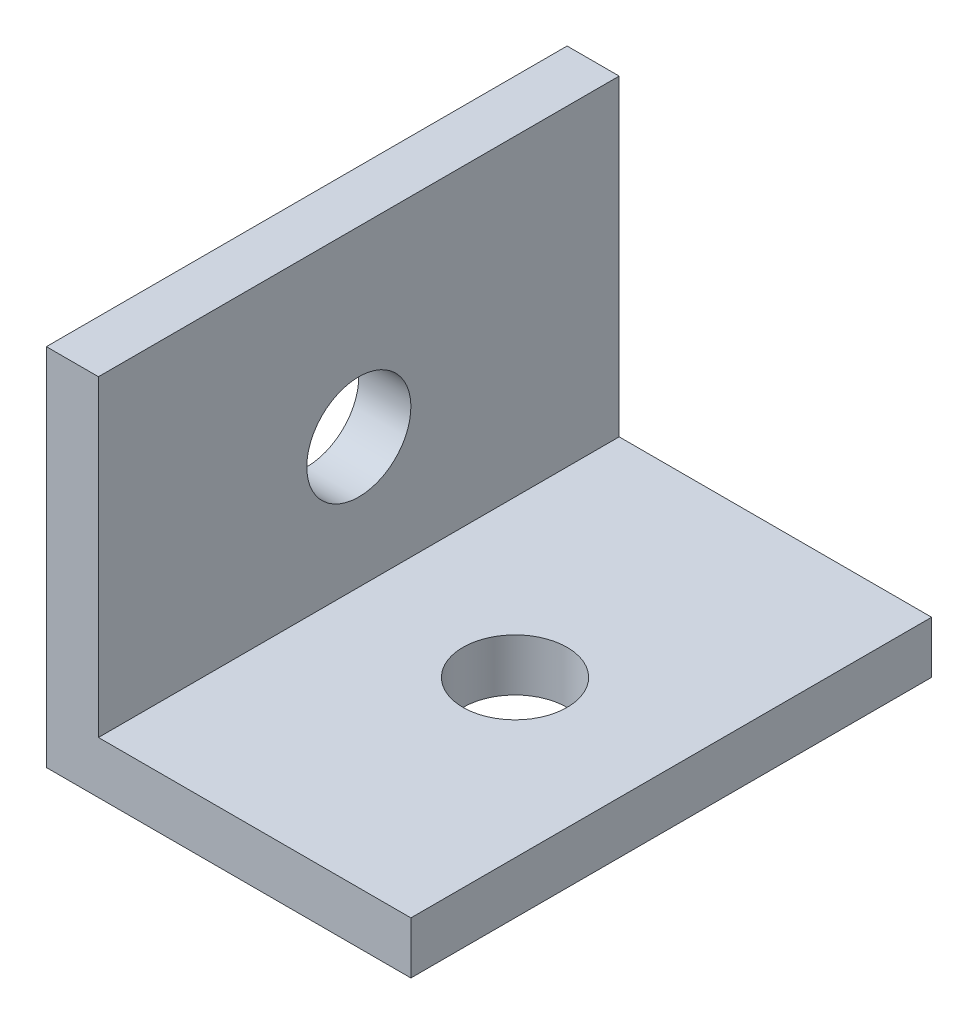
SolidWorks part; units mm, degrees
ref_plane "Front Plane" through (0, 0, 0) normal (0, 0, 1) x (1, 0, 0)
ref_plane "Top Plane" through (0, 0, 0) normal (0, 1, 0) x (1, 0, 0)
ref_plane "Right Plane" through (0, 0, 0) normal (1, 0, 0) x (0, 0, -1)
sketch "Sketch1" plane through (0, 0, 0) normal (0, 0, 1) x (1, 0, 0)
  line L0 (0, 0) -> (35, 0)
  line L1 (35, 0) -> (35, 5)
  line L2 (35, 5) -> (5, 5)
  line L3 (5, 5) -> (5, 35)
  line L4 (5, 35) -> (0, 35)
  line L5 (0, 35) -> (0, 0)
  dimension "D1" = 35
  dimension "D2" = 35
  dimension "D3" = 5
  dimension "D4" = 5
extrude "Boss-Extrude1" add sketch "Sketch1" along normal blind 50
sketch "Sketch2" plane through (0, 5, 0) normal (0, 1, 0) x (1, 0, 0)
  line L0 (35, -25) -> (5, -25)
  line L1 (35, -50) -> (35, 0) construction
  line L2 (5, -50) -> (5, 0) construction
  circle A0 centre (20, -25) radius 5
  dimension "D1" = 10
sketch "Sketch3" plane through (0, 0, 0) normal (-1, 0, 0) x (0, 0, 1)
  line L0 (25, 35) -> (25, 0)
  line L1 (50, 35) -> (0, 35) construction
  line L2 (50, 0) -> (0, 0) construction
  circle A0 centre (25, 17.5) radius 4.9992
extrude "Cut-Extrude1" cut sketch "Sketch3" against normal through all contours L0 A0 | L0 A0
extrude "Cut-Extrude2" cut sketch "Sketch2" against normal blind 50 contours L0 A0 | L0 A0
